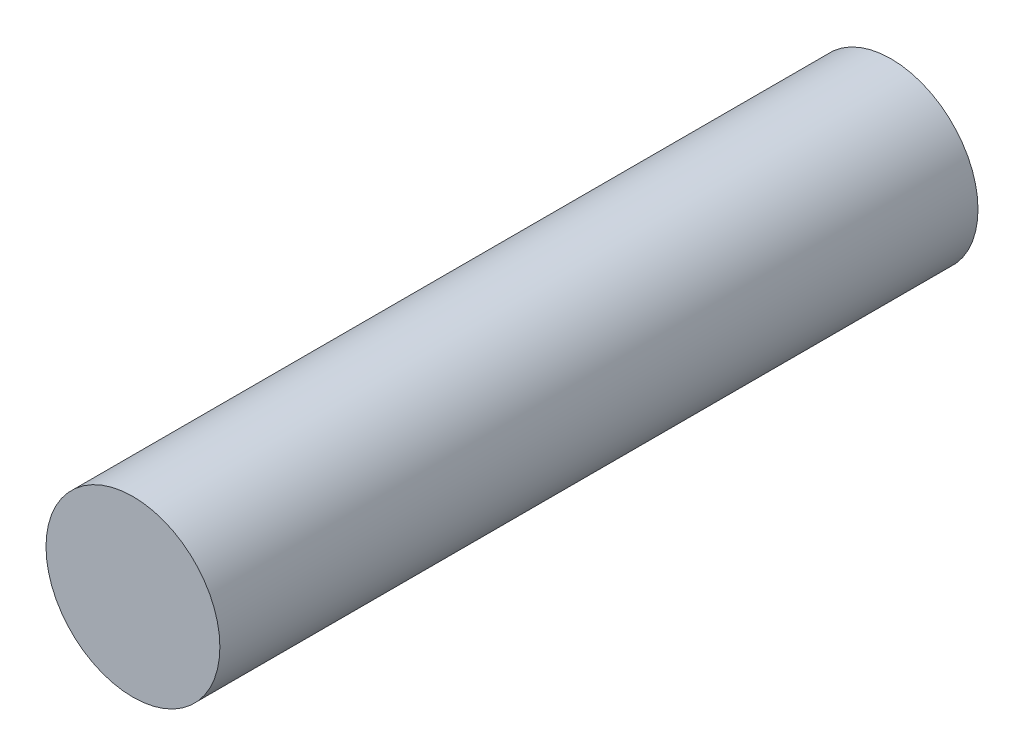
SolidWorks part; units mm, degrees
ref_plane "Front" through (0, 0, 0) normal (0, 0, 1) x (1, 0, 0)
ref_plane "Top" through (0, 0, 0) normal (0, 1, 0) x (1, 0, 0)
ref_plane "Right" through (0, 0, 0) normal (1, 0, 0) x (0, 0, -1)
other "Configuration Table"
sketch "Sketch1" plane through (0, 0, 0) normal (0, 0, 1) x (1, 0, 0)
  circle A0 centre (0, 0) radius 12.5
  dimension "D1" = 25
extrude "Boss-Extrude1" add sketch "Sketch1" along normal mid plane 109
